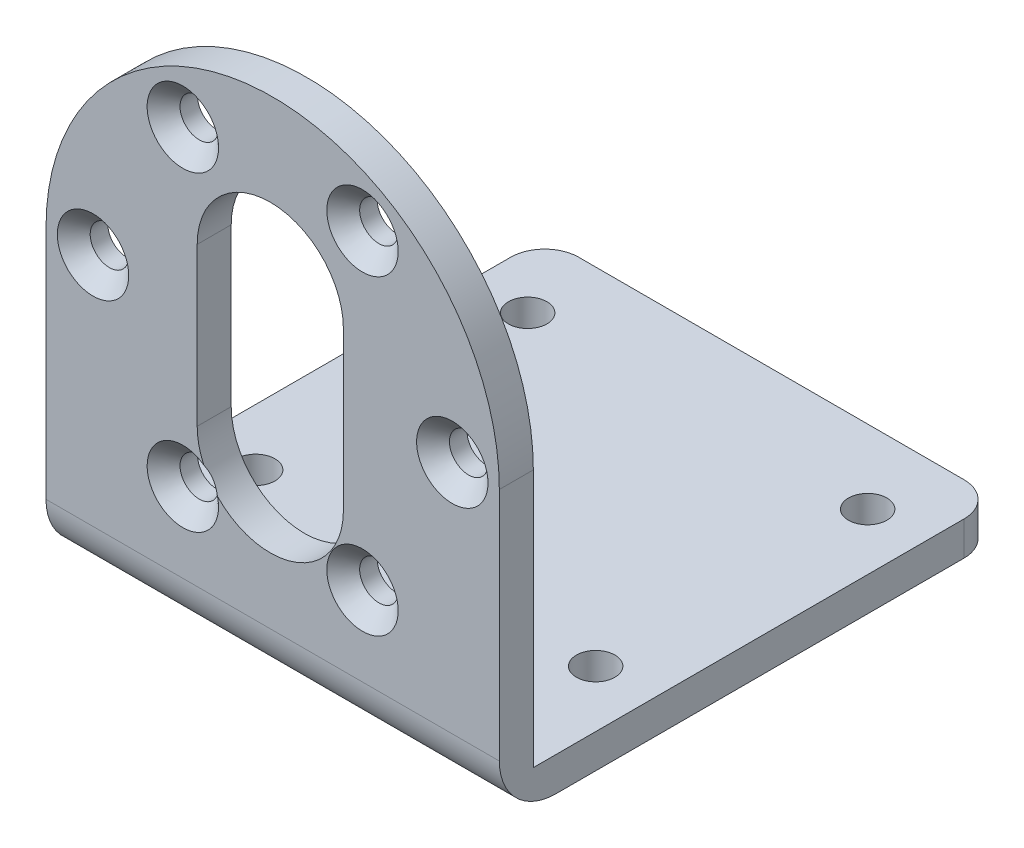
SolidWorks part; units mm, degrees
ref_plane "Front Plane" through (0, 0, 0) normal (0, 0, 1) x (1, 0, 0)
ref_plane "Top Plane" through (0, 0, 0) normal (0, 1, 0) x (1, 0, 0)
ref_plane "Right Plane" through (0, 0, 0) normal (1, 0, 0) x (0, 0, -1)
sketch "Sketch2" plane through (0, 0, 0) normal (0, 0, 1) x (1, 0, 0)
  line L0 (0, 0) -> (40, 0)
  line L1 (40, 0) -> (40, 25.75)
  line L2 (0, 25.75) -> (0, 0)
  line L3 (26.2408, 17.25) -> (26.2408, 31.15)
  line L4 (13.3408, 31.15) -> (13.3408, 17.25)
  arc A0 (40, 25.75) -> (0, 25.75) centre (20, 25.75) ccw
  arc A4 (13.3408, 17.25) -> (26.2408, 17.25) centre (19.7908, 17.25) ccw
  arc A5 (26.2408, 31.15) -> (13.3408, 31.15) centre (19.7908, 31.15) ccw
  point P9 (19.7908, 37.6)
  point P11 (20, 45.75)
  point P14 (19.7908, 10.8)
  point P15 (20, 0)
  point P16 (42.772, 9.8642)
  point P17 (19.1242, 7.6894)
  dimension "D2" = 6.45
  dimension "D3" = 8.15
  dimension "D1" = 40
  dimension "D4" = 26.8
  dimension "D5" = 10.8
extrude "Boss-Extrude1" add sketch "Sketch2" against normal blind 3
hole_wizard "CSK for M3 Flat Head Machine Screw1" positions "Sketch5" profile "Sketch4" countersink size "M3" standard "ANSI Metric" end condition through all
sketch "Sketch5" plane through (0, 0, 0) normal (0, 0, 1) x (1, 0, 0)
  point P0 (4.15, 25.75)
  point P8 (12.075, 39.4765)
  point P9 (27.925, 39.4765)
  point P10 (35.85, 25.75)
  point P11 (27.925, 12.0235)
  point P12 (12.075, 12.0235)
  dimension "D2" = 4.15
  dimension "D1" = 6
sketch "Sketch4" plane through (4.15, 25.75, 0) normal (1, 0, 0) x (0, -1, 0)
  line L0 (0, 0) -> (0, 3)
  line L1 (0, 3) -> (1.7, 3)
  line L2 (1.7, 3) -> (1.7, 1.45)
  line L3 (1.7, 1.45) -> (3.15, 0)
  line L5 (3.15, 0) -> (0, 0)
  line L6 (-1.7, 1.45) -> (-3.15, 0) construction
  line L11 (0, -6.35) -> (0, 107.95) construction
  dimension "Thru Hole Dia." = 3.4
  dimension "Thru Hole Depth" = 3
  dimension "Near C'Sink Dia." = 6.3
  dimension "Near C'Sink Angle" = 90
sketch "Sketch6" plane through (0, 0, -3) normal (0, 0, -1) x (-1, 0, 0)
  line L0 (0, 25.75) -> (0, 0) construction
  line L1 (-40, 0) -> (0, 0)
  line L2 (-40, 0) -> (-40, 3)
  line L3 (-40, 3) -> (0, 3)
  line L4 (0, 0) -> (0, 3)
  dimension "D1" = 3
extrude "Boss-Extrude2" add sketch "Sketch6" along normal offset from surface (41 mm away) 44 up to face at (7.3, 25.75, 0)
sketch "Sketch7" plane through (0, 0, 0) normal (0, -1, 0) x (1, 0, 0)
  line L0 (0, -44) -> (40, -44) construction
  line L1 (20, -44) -> (20, 0) construction
  line L2 (0, 0) -> (40, 0) construction
  line L3 (0, -44) -> (0, 0) construction
  circle A0 centre (5, -37.5) radius 1.7
  circle A3 centre (5, -13.5) radius 1.7
  circle A4 centre (35, -37.5) radius 1.7
  circle A5 centre (35, -13.5) radius 1.7
  dimension "D1" = 6.5
  dimension "D4" = 3.4
  dimension "D2" = 5
  dimension "D3" = 24
extrude "Cut-Extrude1" cut sketch "Sketch7" against normal up to surface (3 mm away) up to face at (20, 3, -23.5)
fillet "Fillet1" radius 3 2 edges at (0, 1.5, -44) (40, 1.5, -44)
fillet "Fillet2" radius 5 1 edges at (20, 0, 0)
